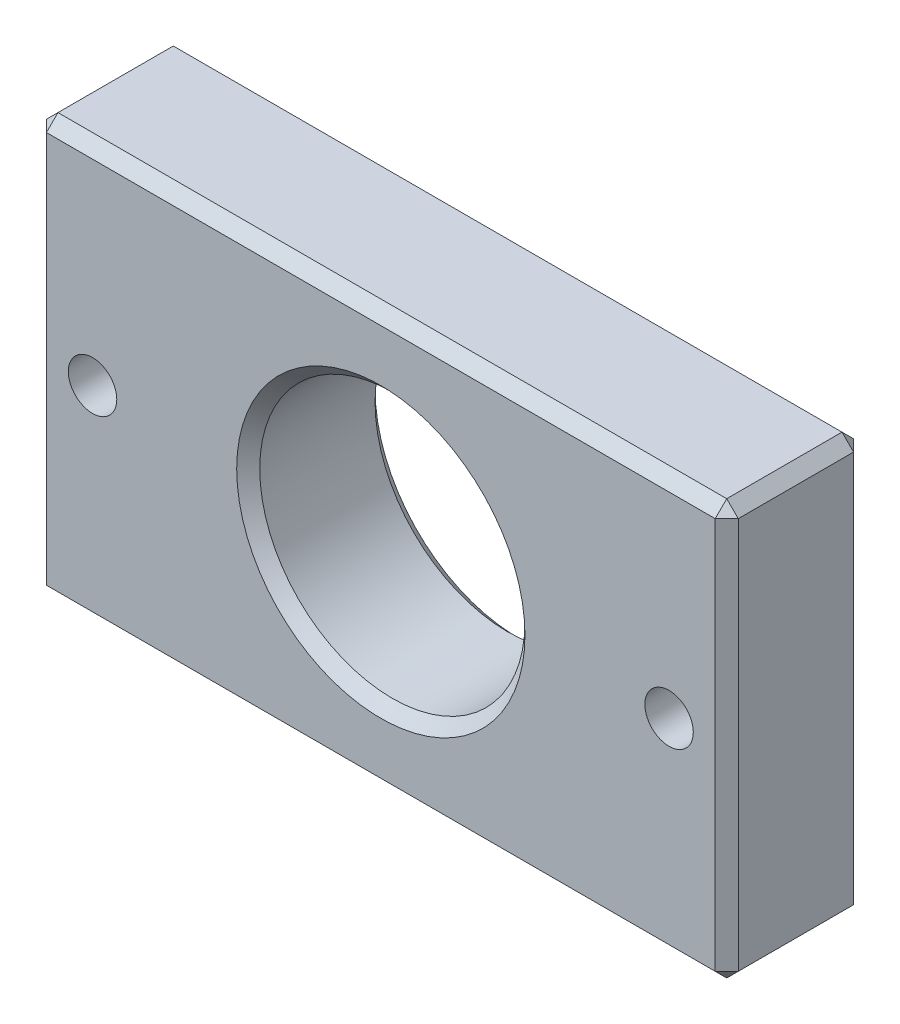
SolidWorks part; units mm, degrees
material "Alliage 1060"
ref_plane "Face" through (0, 0, 0) normal (0, 0, 1) x (1, 0, 0)
ref_plane "Dessus" through (0, 0, 0) normal (0, 1, 0) x (1, 0, 0)
ref_plane "Droite" through (0, 0, 0) normal (1, 0, 0) x (0, 0, -1)
sketch "Esquisse1" plane through (0, 0, 0) normal (0, 0, 1) x (1, 0, 0)
  line L1 (-30, 18) -> (30, 18)
  line L2 (-30, 18) -> (-30, -18)
  line L3 (-30, -18) -> (30, -18)
  line L4 (30, 18) -> (30, -18)
  dimension "D1" = 18
  dimension "D2" = 36
  dimension "D3" = 30
  dimension "D4" = 60
extrude "Boss.-Extru.1" add sketch "Esquisse1" along normal blind 12
sketch "Esquisse2" plane through (0, 0, 12) normal (0, 0, 1) x (1, 0, 0)
  circle A0 centre (0, 0) radius 11.5
extrude "Enlèv. mat.-Extru.1" cut sketch "Esquisse2" against normal up to next
hole_wizard "Trou taraudé M51" positions "Esquisse4" profile "Esquisse3" tap size "M5" standard "Iso" end condition up to next
sketch "Esquisse4" plane through (0, 0, 12) normal (0, 0, 1) x (1, 0, 0)
  point P0 (-25, 0)
  point P2 (25, 0)
  dimension "D1" = 25
  dimension "D2" = 25
cosmetic thread "Filetage de perçage1" parameters "D2"=5
cosmetic thread "Filetage de perçage2" parameters "D2"=5
sketch "Esquisse3" plane through (-25, 0, 12) normal (1, 0, 0) x (0, -1, 0)
  line L0 (0, 0) -> (0, 12)
  line L1 (0, 12) -> (2.1, 12)
  line L2 (2.1, 12) -> (2.1, 0)
  line L5 (2.1, 0) -> (0, 0)
  line L11 (0, -6.35) -> (0, 107.95) construction
  dimension "Diamètre du trou pour taraudage jusqu'au prochain" = 4.2
  dimension "Profondeur du trou pour taraudage jusqu'au prochain" = 12
chamfer "Chanfrein1" distance 1 angle 45 14 edges at (11.5, 0, 0) (11.5, 0, 12) (30, 18, 6) (0, 18, 12) (-30, 18, 6) (0, 18, 0) (-30, 0, 12) (-30, 0, 0) (-30, -18, 6) (0, -18, 12) (0, -18, 0) (30, -18, 6) (30, 0, 12) (30, 0, 0)
